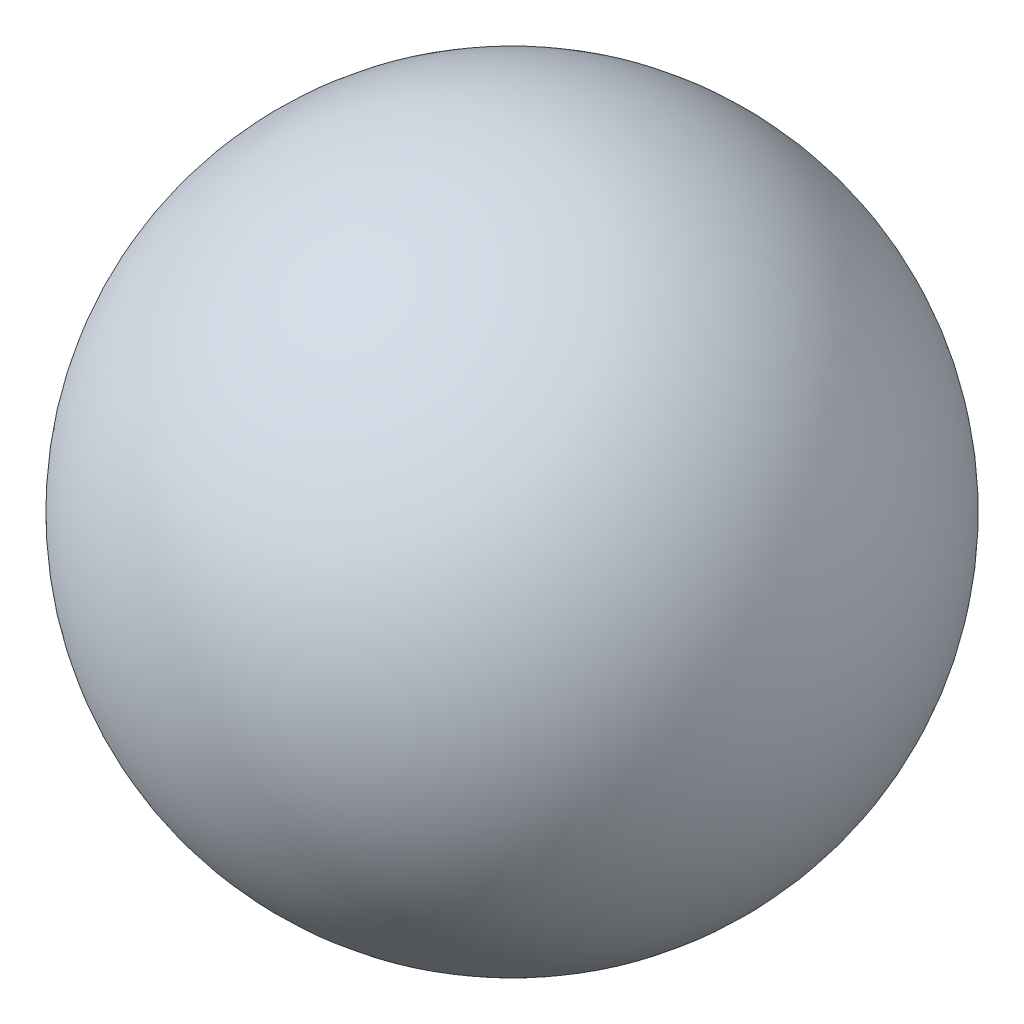
SolidWorks part; units mm, degrees
material "1.7036 (28CrS4)"
ref_plane "Plan de face" through (0, 0, 0) normal (0, 0, 1) x (1, 0, 0)
ref_plane "Plan de dessus" through (0, 0, 0) normal (0, 1, 0) x (1, 0, 0)
ref_plane "Plan de droite" through (0, 0, 0) normal (1, 0, 0) x (0, 0, -1)
sketch "Esquisse1" plane through (0, 0, 0) normal (0, 0, 1) x (1, 0, 0)
  line L0 (0, 8) -> (0, 0)
  line L1 (0, 0) -> (5, 0) construction
  line L2 (0, 0) -> (0, 8) construction
  line L3 (0, 8) -> (5, 8) construction
  line L4 (5, 0) -> (5, 8) construction
  arc A0 (0, 0) -> (0, 8) centre (0, 4) ccw
  dimension "D1" = 4
  dimension "D2" = 8
  dimension "D3" = 5
revolve "Révolution1" add sketch "Esquisse1" angle 360 about L0
